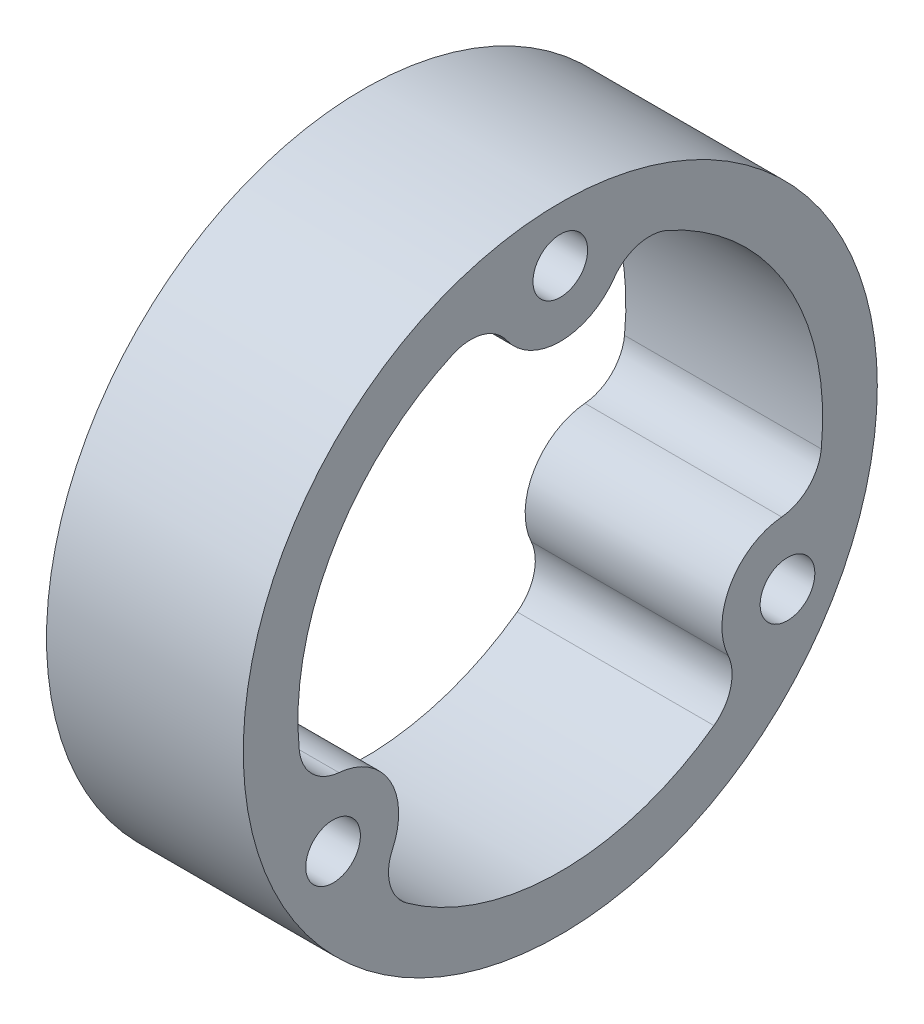
SolidWorks part; units mm, degrees
material "ABS"
ref_plane "前视基准面" through (0, 0, 0) normal (0, 0, 1) x (1, 0, 0)
ref_plane "上视基准面" through (0, 0, 0) normal (0, 1, 0) x (1, 0, 0)
ref_plane "右视基准面" through (0, 0, 0) normal (1, 0, 0) x (0, 0, -1)
other "Configuration Table"
sketch "草图1" plane through (0, 0, 0) normal (1, 0, 0) x (0, 0, -1)
  line L0 (0, 0) -> (0, 12) construction
  circle A19 centre (0, 0) radius 14.5
  arc A20 (-2.9765, 11.625) -> (-11.5558, -3.2348) centre (0, 0) ccw
  circle A36 centre (0, 12) radius 1.25
  circle A37 centre (10.3923, -6) radius 1.25
  circle A38 centre (-10.3923, -6) radius 1.25
  arc A39 (-2.9765, 11.625) -> (2.9765, 11.625) centre (0, 12) ccw
  arc A40 (11.5558, -3.2348) -> (8.5793, -8.3902) centre (10.3923, -6) ccw
  arc A41 (-8.5793, -8.3902) -> (-11.5558, -3.2348) centre (-10.3923, -6) ccw
  arc A42 (-8.5793, -8.3902) -> (8.5793, -8.3902) centre (0, 0) ccw
  arc A44 (11.5558, -3.2348) -> (2.9765, 11.625) centre (0, 0) ccw
  point P11 (0, 0)
  point P17 (0, 0)
  dimension "D1" = 29
  dimension "D2" = 24
  dimension "D3" = 2.5
  dimension "D5" = 3
  dimension "D4" = 6
extrude "凸台-拉伸1" add sketch "草图1" along normal blind 9
fillet "圆角1" radius 2 6 edges at (4.5, 11.625, 2.9765) (4.5, -3.2348, 11.5558) (4.5, -8.3902, -8.5793) (4.5, -3.2348, -11.5558) (4.5, 11.625, -2.9765) (4.5, -8.3902, 8.5793)
